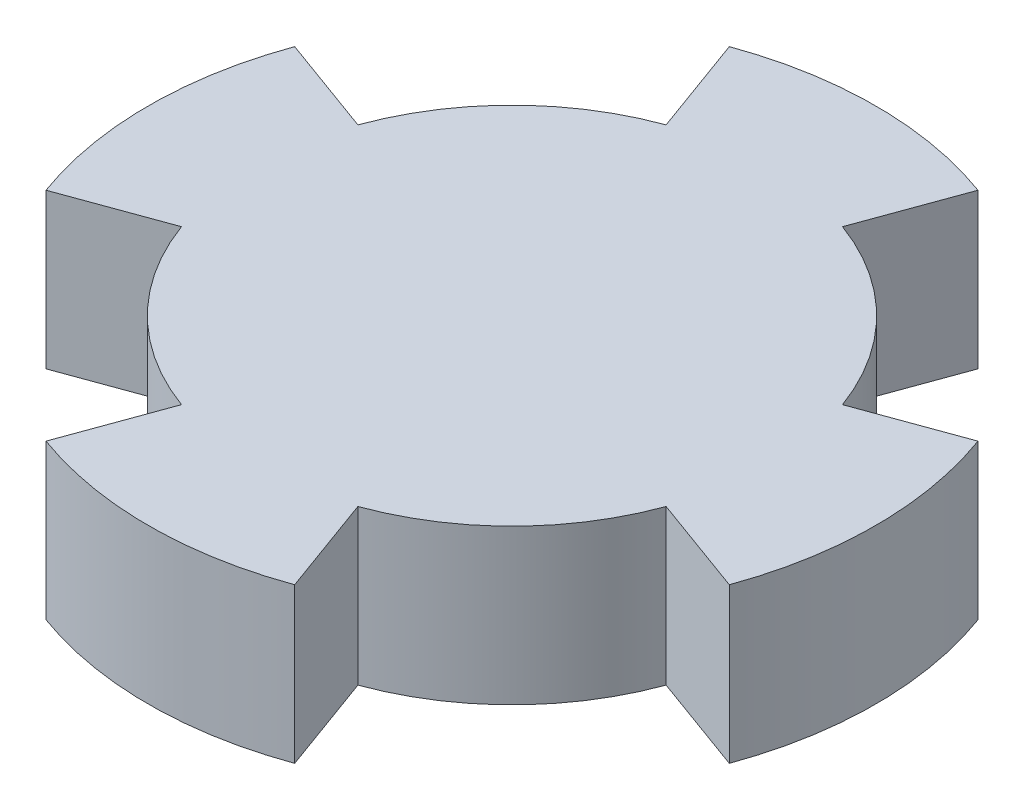
SolidWorks part; units mm, degrees
ref_plane "前视基准面" through (0, 0, 0) normal (0, 0, 1) x (1, 0, 0)
ref_plane "上视基准面" through (0, 0, 0) normal (0, 1, 0) x (1, 0, 0)
ref_plane "右视基准面" through (0, 0, 0) normal (1, 0, 0) x (0, 0, -1)
sketch "草图1" plane through (0, 0, 0) normal (0, 1, 0) x (1, 0, 0)
  line L0 (0, 0) -> (-352.5, 0) construction
  line L1 (0, 0) -> (0, -352.5) construction
  line L2 (0, 0) -> (-331.2416, -120.5621) construction
  line L3 (-331.2416, -120.5621) -> (-234.9232, -85.505)
  line L4 (0, 0) -> (-120.5621, -331.2416) construction
  line L5 (-85.505, -234.9232) -> (-120.5621, -331.2416)
  line L6 (-120.5621, 331.2416) -> (-85.505, 234.9232)
  line L7 (-234.9232, 85.505) -> (-331.2416, 120.5621)
  line L8 (0, 0) -> (0, 352.5) construction
  line L9 (0, 0) -> (-352.5, 0) construction
  line L10 (0, 0) -> (-120.5621, 331.2416) construction
  line L11 (0, 0) -> (-331.2416, 120.5621) construction
  line L12 (331.2416, 120.5621) -> (234.9232, 85.505)
  line L13 (85.505, 234.9232) -> (120.5621, 331.2416)
  line L14 (0, 0) -> (352.5, 0) construction
  line L15 (0, 0) -> (0, 352.5) construction
  line L16 (0, 0) -> (331.2416, 120.5621) construction
  line L17 (0, 0) -> (120.5621, 331.2416) construction
  line L18 (120.5621, -331.2416) -> (85.505, -234.9232)
  line L19 (234.9232, -85.505) -> (331.2416, -120.5621)
  line L20 (0, 0) -> (0, -352.5) construction
  line L21 (0, 0) -> (352.5, 0) construction
  line L22 (0, 0) -> (120.5621, -331.2416) construction
  line L23 (0, 0) -> (331.2416, -120.5621) construction
  arc A0 (-120.5621, -331.2416) -> (0, -352.5) centre (0, 0) ccw
  arc A2 (-234.9232, -85.505) -> (-85.505, -234.9232) centre (0, 0) ccw
  arc A3 (-120.5621, -331.2416) -> (0, -352.5) centre (0, 0) ccw
  arc A4 (-234.9232, -85.505) -> (-85.505, -234.9232) centre (0, 0) ccw
  arc A5 (-352.5, 0) -> (-331.2416, -120.5621) centre (0, 0) ccw
  arc A6 (-331.2416, 120.5621) -> (-352.5, 0) centre (0, 0) ccw
  arc A7 (-85.505, 234.9232) -> (-234.9232, 85.505) centre (0, 0) ccw
  arc A8 (-331.2416, 120.5621) -> (-352.5, 0) centre (0, 0) ccw
  arc A9 (-85.505, 234.9232) -> (-234.9232, 85.505) centre (0, 0) ccw
  arc A10 (0, 352.5) -> (-120.5621, 331.2416) centre (0, 0) ccw
  arc A11 (120.5621, 331.2416) -> (0, 352.5) centre (0, 0) ccw
  arc A12 (234.9232, 85.505) -> (85.505, 234.9232) centre (0, 0) ccw
  arc A13 (120.5621, 331.2416) -> (0, 352.5) centre (0, 0) ccw
  arc A14 (234.9232, 85.505) -> (85.505, 234.9232) centre (0, 0) ccw
  arc A15 (352.5, 0) -> (331.2416, 120.5621) centre (0, 0) ccw
  arc A16 (331.2416, -120.5621) -> (352.5, 0) centre (0, 0) ccw
  arc A17 (85.505, -234.9232) -> (234.9232, -85.505) centre (0, 0) ccw
  arc A18 (331.2416, -120.5621) -> (352.5, 0) centre (0, 0) ccw
  arc A19 (85.505, -234.9232) -> (234.9232, -85.505) centre (0, 0) ccw
  arc A20 (0, -352.5) -> (120.5621, -331.2416) centre (0, 0) ccw
  point P29 (0, 0)
  dimension "D1" = 352.5
  dimension "D2" = 250
  dimension "D5" = 4
  dimension "D3" = 20
  dimension "D4" = 20
extrude "凸台-拉伸1" add sketch "草图1" along normal blind 150 contours A0 A20 L18 A17 L19 A16 A15 L12 A12 L13 A11 A10 L6 A7 L7 A6 A5 L3 A2 L5
